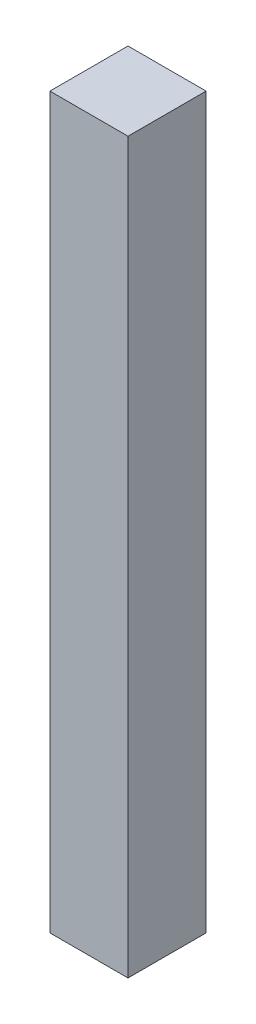
SolidWorks part; units mm, degrees
ref_plane "前视基准面" through (0, 0, 0) normal (0, 0, 1) x (1, 0, 0)
ref_plane "上视基准面" through (0, 0, 0) normal (0, 1, 0) x (1, 0, 0)
ref_plane "右视基准面" through (0, 0, 0) normal (1, 0, 0) x (0, 0, -1)
sketch "草图1" plane through (0, 0, 0) normal (0, 1, 0) x (1, 0, 0)
  line L1 (-15, -15) -> (15, -15)
  line L2 (-15, -15) -> (-15, 15)
  line L3 (-15, 15) -> (15, 15)
  line L4 (15, -15) -> (15, 15)
  line L5 (0, 15) -> (0, -15) construction
  line L6 (-15, 0) -> (15, 0) construction
  point P0 (0, 0)
  dimension "D1" = 30
  dimension "D2" = 30
extrude "凸台-拉伸1" add sketch "草图1" along normal blind 280
